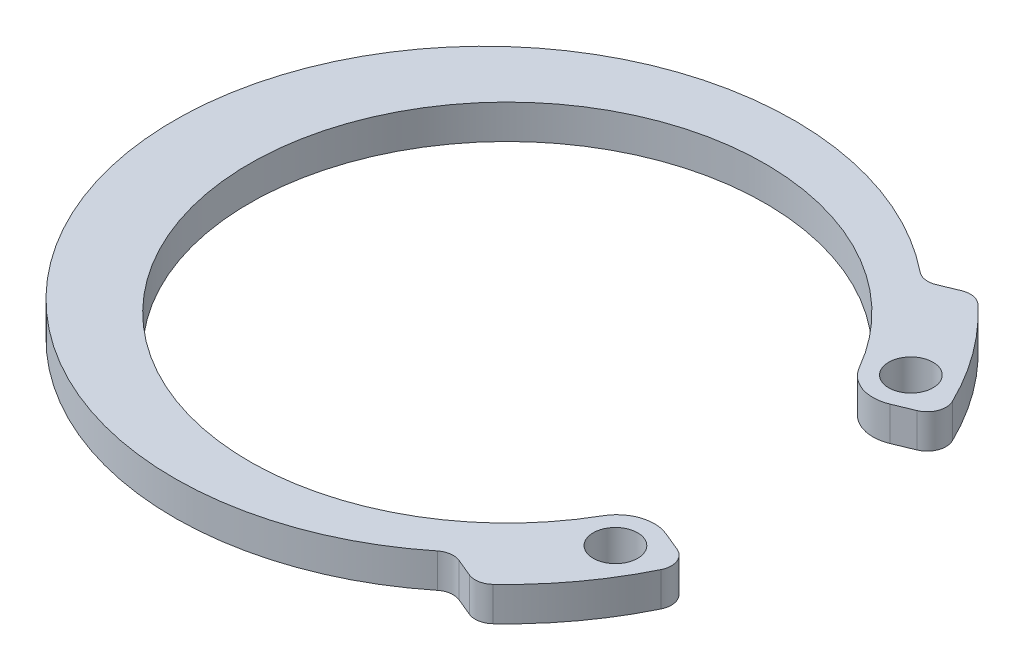
SolidWorks part; units mm, degrees
ref_plane "Front Plane" through (0, 0, 0) normal (0, 0, 1) x (1, 0, 0)
ref_plane "Top Plane" through (0, 0, 0) normal (0, 1, 0) x (1, 0, 0)
ref_plane "Right Plane" through (0, 0, 0) normal (1, 0, 0) x (0, 0, -1)
sketch "Sketch1" plane through (0, 0, 0) normal (0, 1, 0) x (1, 0, 0)
  line L0 (0, 0) -> (4.5961, 5.9898) construction
  line L1 (4.5961, 5.9898) -> (5.9354, 7.7352) construction
  line L2 (0, 0) -> (6.9753, 2.8893) construction
  line L3 (6.9753, 2.8893) -> (9.0078, 3.7312) construction
  line L4 (0, 0) -> (6.9753, -2.8893) construction
  line L5 (6.9753, -2.8893) -> (9.0078, -3.7312) construction
  line L6 (0, 0) -> (4.5961, -5.9898) construction
  line L7 (4.5961, -5.9898) -> (5.9354, -7.7352) construction
  line L8 (7.4716, -5.7332) -> (0, 0) construction
  line L9 (0, 0) -> (9.75, 0) construction
  line L10 (9.0078, 3.7312) -> (9.0078, -3.7312) construction
  line L11 (9.0078, -3.7312) -> (5.9354, -7.7352) construction
  line L12 (9.0078, 3.7312) -> (5.9354, 7.7352) construction
  line L13 (7.4716, 5.7332) -> (0, 0) construction
  line L14 (-7.55, 0) -> (-9.75, 0) construction
  circle A0 centre (0, 0) radius 9.75 construction
  circle A1 centre (0, 0) radius 7.55 construction
  arc A4 (7.9916, 3.3102) -> (6.8625, 5.2658) centre (0, 0) ccw construction
  arc A7 (7.9916, -3.3102) -> (6.8625, -5.2658) centre (0, 0) cw construction
  circle A8 centre (7.4911, -4.325) radius 0.65 construction
  circle A9 centre (7.4911, 4.325) radius 0.65 construction
  point P20 (9.0078, 0)
  dimension "Ring OD" = 19.5
  dimension "R" = 1.3
  dimension "D1" = 30
  dimension "D3" = 45
  dimension "S" = 2.2
sketch "Sketch2" plane through (0, 0, 0) normal (1, 0, 0) x (0, 0, -1)
  line L3 (9.75, 0) -> (-9.75, 0) construction
  line L7 (9.75, 0.5) -> (9.75, -0.5) construction
  dimension "Ring Thickness" = 1
sketch "Sketch3" plane through (0, 0, 0) normal (0, 1, 0) x (1, 0, 0)
  line L1 (-9.75, 0) -> (-7.55, 0) construction
  line L2 (6.9753, -2.8893) -> (9.0078, -3.7312) construction
  line L3 (4.5961, -5.9898) -> (5.9354, -7.7352) construction
  line L5 (5.5732, 6.9898) -> (6.0961, 7.2064)
  line L6 (7.9267, 3.2833) -> (8.4845, 3.5144)
  line L7 (7.9267, -3.2833) -> (8.4845, -3.5144)
  line L8 (5.5732, -6.9898) -> (6.0961, -7.2064)
  line L9 (4.5961, 5.9898) -> (5.9354, 7.7352) construction
  line L10 (6.9753, 2.8893) -> (9.0078, 3.7312) construction
  line L11 (0, 0) -> (6.9753, 2.8893) construction
  arc A1 (6.5512, 3.7528) -> (6.5512, -3.7528) centre (0, 0) ccw
  circle A2 centre (0, 0) radius 7.55 construction
  arc A3 (5.0178, 7.0696) -> (5.0178, -7.0696) centre (-0.674, 0) ccw
  circle A4 centre (0, 0) radius 9.75 construction
  arc A6 (6.6836, 7.0987) -> (8.7687, 4.263) centre (0, 0) cw
  arc A7 (6.0961, -7.2064) -> (6.6836, -7.0987) centre (6.3066, -6.6983) ccw
  arc A8 (6.6836, -7.0987) -> (8.7687, -4.263) centre (0, 0) ccw
  circle A9 centre (7.4911, -4.325) radius 0.65
  circle A10 centre (7.4911, 4.325) radius 0.65
  circle A11 centre (7.4911, 4.325) radius 0.65 construction
  circle A12 centre (7.4911, -4.325) radius 0.65 construction
  arc A13 (5.0178, -7.0696) -> (5.5732, -6.9898) centre (5.3627, -7.498) cw
  arc A14 (8.4845, -3.5144) -> (8.7687, -4.263) centre (8.274, -4.0225) cw
  arc A15 (7.9267, -3.2833) -> (6.5512, -3.7528) centre (7.5057, -4.2996) ccw
  arc A16 (7.9267, 3.2833) -> (6.5512, 3.7528) centre (7.5057, 4.2996) cw
  arc A17 (8.4845, 3.5144) -> (8.7687, 4.263) centre (8.274, 4.0225) ccw
  arc A18 (6.0961, 7.2064) -> (6.6836, 7.0987) centre (6.3066, 6.6983) cw
  arc A19 (5.0178, 7.0696) -> (5.5732, 6.9898) centre (5.3627, 7.498) ccw
  arc A20 (7.9916, 3.3102) -> (6.8625, 5.2658) centre (0, 0) ccw construction
  arc A21 (6.8625, -5.2658) -> (7.9916, -3.3102) centre (0, 0) ccw construction
  point P24 (5.2658, 6.8625)
  point P30 (5.2658, -6.8625)
  dimension "D1" = 0.55
  dimension "D2" = 1.1
extrude "Boss-Extrude1" add sketch "Sketch3" along normal up to vertex (0.5 mm away) and the other way up to vertex (0.5 mm away) up to point (0, 0.5, -9.75) other way up to point (0, -0.5, -9.75)
sketch "Sketch4" plane through (0, 0, 0) normal (0, 1, 0) x (1, 0, 0)
  line L0 (0, -9.051) -> (0, 9.051) construction
  arc A0 (5.0178, 7.0696) -> (5.0178, -7.0696) centre (-0.674, 0) ccw construction
  point P7 (0, 0)
  point P9 (0, -9.051)
equation "\"D1@Sketch3\"=\"S@Sketch1\"/4"
equation "\"D2@Sketch3\"=\"S@Sketch1\"/2"
